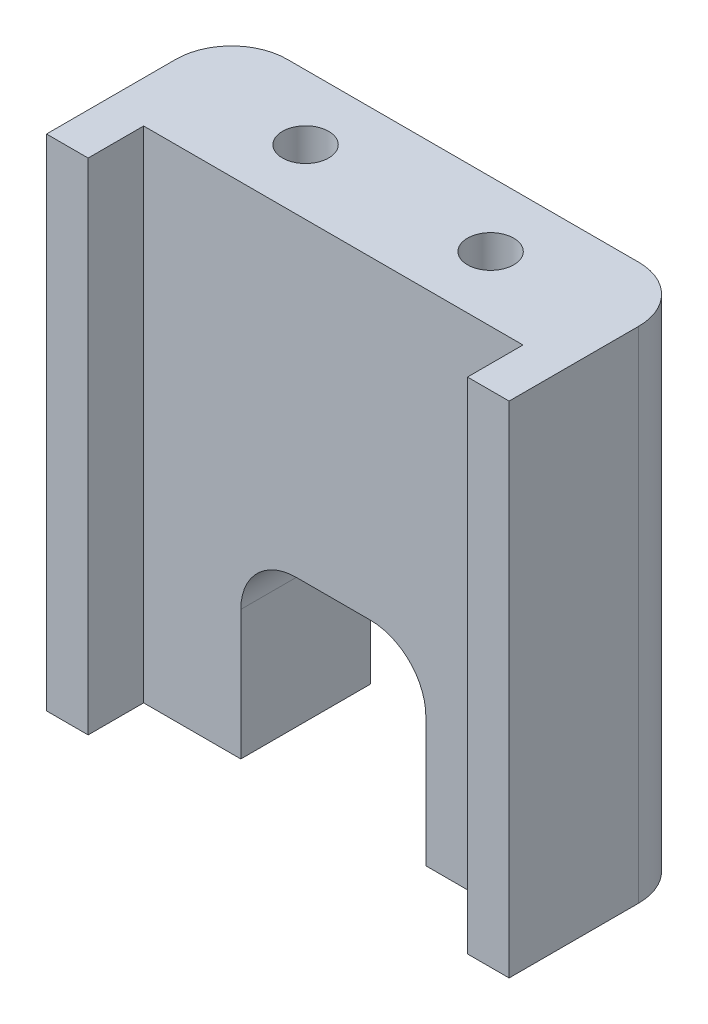
SolidWorks part; units mm, degrees
ref_plane "정면" through (0, 0, 0) normal (0, 0, 1) x (1, 0, 0)
ref_plane "윗면" through (0, 0, 0) normal (0, 1, 0) x (1, 0, 0)
ref_plane "우측면" through (0, 0, 0) normal (1, 0, 0) x (0, 0, -1)
sketch "스케치1" plane through (0, 0, 0) normal (0, 0, 1) x (1, 0, 0)
  line L1 (0, 0) -> (25, 0)
  line L2 (0, 0) -> (0, 27)
  line L3 (0, 27) -> (25, 27)
  line L4 (25, 0) -> (25, 27)
  dimension "D1" = 27
  dimension "D2" = 25
extrude "보스-돌출1" add sketch "스케치1" along normal blind 10
sketch "스케치2" plane through (0, 0, 10) normal (0, 0, 1) x (1, 0, 0)
  line L0 (25, 27) -> (0, 27) construction
  line L1 (2.25, 27) -> (22.75, 27)
  line L2 (2.25, 27) -> (2.25, 0)
  line L3 (2.25, 0) -> (22.75, 0)
  line L4 (22.75, 27) -> (22.75, 0)
  line L5 (0, 0) -> (25, 0) construction
  line L7 (0, 27) -> (0, 0) construction
  dimension "D1" = 20.5
  dimension "D2" = 2.25
extrude "컷-돌출1" cut sketch "스케치2" against normal blind 3
sketch "스케치3" plane through (0, 27, 0) normal (0, 1, 0) x (1, 0, 0)
  line L0 (7.5, -3.5) -> (17.5, -3.5) construction
  line L1 (25, 0) -> (0, 0) construction
  circle A0 centre (7.5, -3.5) radius 1.25
  circle A1 centre (17.5, -3.5) radius 1.25
  point P6 (12.5, 0)
  point P7 (12.5, -3.5)
  dimension "D2" = 10
  dimension "D3" = 2.5
  dimension "D1" = 3.5
extrude "컷-돌출2" cut sketch "스케치3" against normal blind 12
sketch "스케치4" plane through (0, 0, 0) normal (0, -1, 0) x (1, 0, 0)
  line L0 (3.5, 3.5) -> (21.5, 3.5) construction
  line L1 (0, 0) -> (25, 0) construction
  circle A0 centre (3.5, 3.5) radius 1.25
  circle A1 centre (21.5, 3.5) radius 1.25
  point P4 (12.5, 0)
  point P5 (12.5, 3.5)
  dimension "D2" = 2.5
  dimension "D3" = 3.5
  dimension "D1" = 18
extrude "컷-돌출3" cut sketch "스케치4" against normal blind 12
sketch "스케치5" plane through (0, 0, 0) normal (0, 0, -1) x (-1, 0, 0)
  line L0 (0, 0) -> (-25, 0) construction
  line L1 (-17.5, 0) -> (-7.5, 0)
  line L2 (-17.5, 0) -> (-17.5, 10)
  line L3 (-17.5, 10) -> (-7.5, 10)
  line L4 (-7.5, 0) -> (-7.5, 10)
  line L5 (0, 27) -> (0, 0) construction
  dimension "D1" = 10
  dimension "D2" = 10
  dimension "D3" = 7.5
extrude "컷-돌출4" cut sketch "스케치5" against normal blind 12
fillet "필렛1" radius 3 4 edges at (7.5, 10, 3.5) (17.5, 10, 3.5) (0, 13.5, 0) (25, 13.5, 0)
